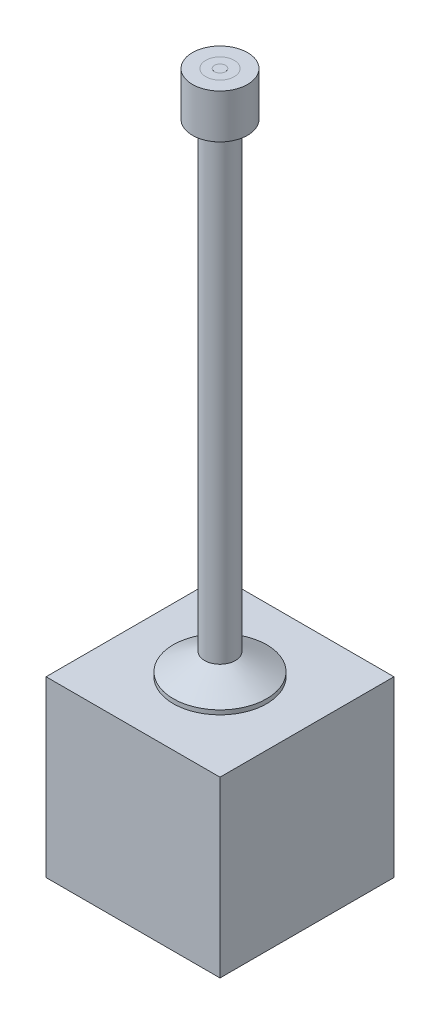
SolidWorks part; units mm, degrees
ref_plane "Alzado" through (0, 0, 0) normal (0, 0, 1) x (1, 0, 0)
ref_plane "Planta" through (0, 0, 0) normal (0, 1, 0) x (1, 0, 0)
ref_plane "Vista lateral" through (0, 0, 0) normal (1, 0, 0) x (0, 0, -1)
sketch "Croquis1" plane through (0, 0, 0) normal (0, 0, 1) x (1, 0, 0)
  line L0 (0, -22.5273) -> (0, 60.571) construction
  line L1 (5.375, 0) -> (5.375, 0.5)
  line L2 (5.375, 0.5) -> (1.78, 2.5)
  line L3 (1.78, 2.5) -> (1.78, 54.5)
  line L4 (1.78, 54.5) -> (3.1718, 55.5)
  line L5 (3.1718, 55.5) -> (3.1718, 60.571)
  line L6 (1.375, 54.9422) -> (1.375, 0)
  line L7 (1.375, 0) -> (5.375, 0)
  line L8 (0.375, 0) -> (0.375, 54.9422)
  line L9 (0.375, 54.9422) -> (0.635, 60.571)
  line L10 (0.375, 0) -> (0, 0)
  line L11 (0, 60.571) -> (0, 0)
  line L12 (0, 60.9797) -> (0, 62.2297) construction
  line L13 (3.1718, 60.571) -> (1.635, 60.571)
  line L14 (0.4604, 60.571) -> (-0.4604, 60.571) construction
  line L23 (1.375, 54.9422) -> (1.635, 60.571)
  line L26 (0.635, 60.571) -> (0.4424, 60.571)
  line L27 (0.4424, 60.571) -> (0, 60.571)
  dimension "D1" = 55
  dimension "D2" = 10.75
  dimension "D3" = 2
  dimension "D4" = 0.5
  dimension "D5" = 0.75
  dimension "D6" = 2.75
  dimension "D7" = 3.56
  dimension "D8" = 1
revolve "Revolución1" add sketch "Croquis1" angle 360 about L11
sketch "Croquis3" plane through (0, 0, 0) normal (0, 0, 1) x (1, 0, 0)
  line L0 (0, 55.5) -> (0, 0) construction
  line L1 (0.375, 54.9422) -> (0.635, 60.571)
  line L2 (0.635, 60.571) -> (-0.635, 60.571) construction
  line L3 (0.635, 60.571) -> (-0.635, 60.571) construction
  line L4 (0.635, 60.571) -> (1.635, 60.571)
  line L6 (0.635, 60.571) -> (0.4424, 60.571)
  line L7 (0.375, 0) -> (0.375, 54.9422)
  line L8 (0, 0) -> (0.375, 0)
  line L9 (0, 60.571) -> (0, 0)
  line L10 (0.375, 54.9422) -> (0.635, 60.571)
  line L12 (0.4424, 60.571) -> (0, 60.571)
  line L13 (0.375, 0) -> (0.375, 54.9422)
  line L20 (3.1718, 55.5) -> (3.1718, 60.571)
  line L21 (1.78, 54.5) -> (3.1718, 55.5)
  line L22 (1.78, 2.5) -> (1.78, 54.5)
  line L23 (5.375, 0.5) -> (1.78, 2.5)
  line L24 (5.375, 0) -> (5.375, 0.5)
  line L25 (1.375, 0) -> (5.375, 0)
  line L26 (1.375, 54.9422) -> (1.375, 0)
  line L27 (1.635, 60.571) -> (1.375, 54.9422)
  line L28 (1.635, 60.571) -> (1.375, 54.9422)
  line L29 (3.1718, 60.571) -> (1.635, 60.571)
  line L33 (0.375, 0) -> (1.375, 0)
  line L34 (1.375, 54.9422) -> (1.375, 0)
  point P1 (0, 0)
  point P21 (0, 0)
  dimension "D1" = 0
  dimension "D2" = 0
revolve "Revolución2" add sketch "Croquis3" angle 360 about L0
sketch "Croquis4" plane through (0, 0, 0) normal (0, -1, 0) x (1, 0, 0)
  line L1 (-10, -10) -> (10, -10)
  line L2 (-10, -10) -> (-10, 10)
  line L3 (-10, 10) -> (10, 10)
  line L4 (10, -10) -> (10, 10)
  line L5 (-10, -10) -> (10, 10) construction
  line L6 (-10, 10) -> (10, -10) construction
  point P0 (0, 0)
  dimension "D1" = 20
  dimension "D2" = 20
extrude "Saliente-Extruir1" add sketch "Croquis4" along normal blind 20 separate body
